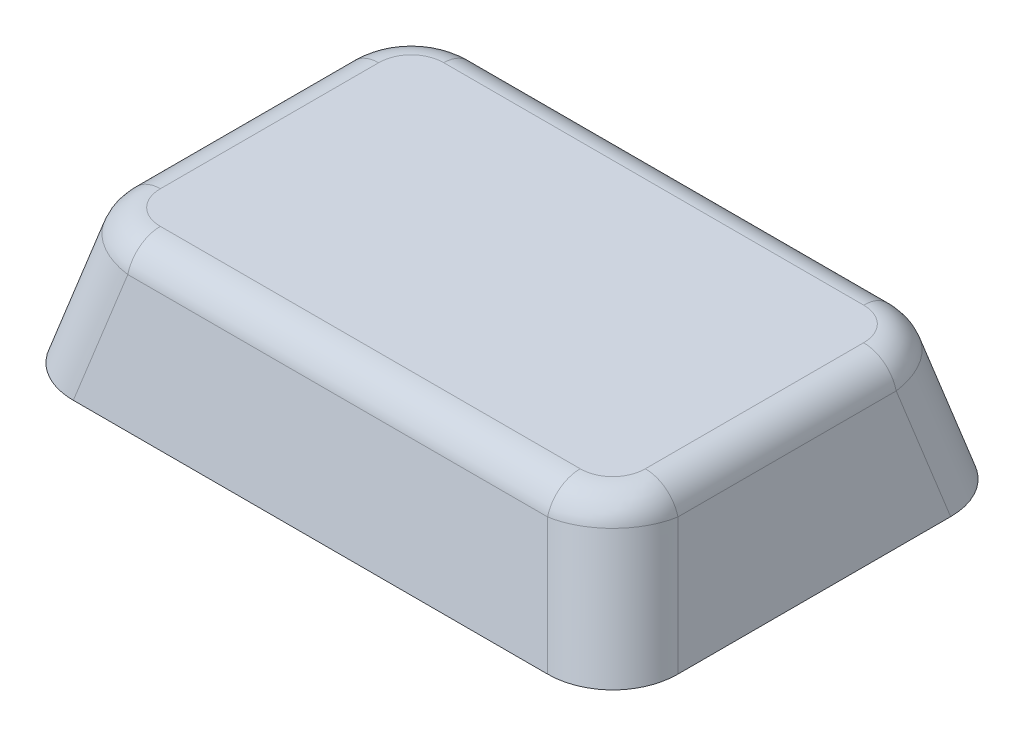
SolidWorks part; units mm, degrees
ref_plane "Front" through (0, 0, 0) normal (0, 0, 1) x (1, 0, 0)
ref_plane "Top" through (0, 0, 0) normal (0, 1, 0) x (1, 0, 0)
ref_plane "Right" through (0, 0, 0) normal (1, 0, 0) x (0, 0, -1)
sketch "草图1" plane through (0, 0, 0) normal (0, 1, 0) x (1, 0, 0)
  line L1 (-4.5, 3) -> (4.5, 3)
  line L2 (-4.5, 3) -> (-4.5, -3)
  line L3 (-4.5, -3) -> (4.5, -3)
  line L4 (4.5, 3) -> (4.5, -3)
  line L5 (-4.5, 3) -> (4.5, -3) construction
  line L6 (-4.5, -3) -> (4.5, 3) construction
  point P0 (0, 0)
  dimension "D1" = 9
  dimension "D2" = 6
ref_plane "基准面1" through (0, 2, 0) normal (0, 1, 0) x (1, 0, 0)
sketch "草图2" plane through (0, 2, 0) normal (0, 1, 0) x (1, 0, 0)
  line L1 (-4, 2.5) -> (4, 2.5)
  line L2 (-4, 2.5) -> (-4, -2.5)
  line L3 (-4, -2.5) -> (4, -2.5)
  line L4 (4, 2.5) -> (4, -2.5)
  line L5 (-4, 2.5) -> (4, -2.5) construction
  line L6 (-4, -2.5) -> (4, 2.5) construction
  point P0 (0, 0)
  dimension "D1" = 8
  dimension "D2" = 5
loft "放样1" add profiles "草图1", "草图2"
fillet "圆角1" radius 1 1 edges
fillet "圆角2" radius 1 1 edges
fillet "圆角3" radius 1 1 edges
fillet "圆角4" radius 1 1 edges
fillet "圆角5" radius 0.5 8 edges
